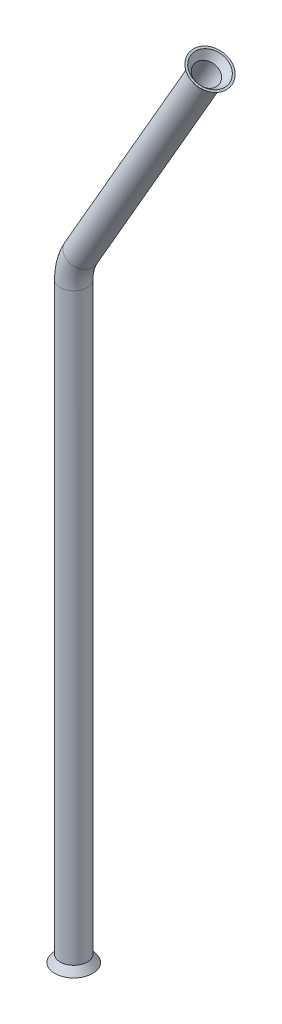
SolidWorks part; units mm, degrees
material "6061-T6 (SS)"
ref_plane "Front Plane" through (0, 0, 0) normal (0, 0, 1) x (1, 0, 0)
ref_plane "Top Plane" through (0, 0, 0) normal (0, 1, 0) x (1, 0, 0)
ref_plane "Right Plane" through (0, 0, 0) normal (1, 0, 0) x (0, 0, -1)
sketch "Sketch1" plane through (0, 0, 0) normal (0, 1, 0) x (1, 0, 0)
  circle A0 centre (0, 0) radius 4.826
  circle A1 centre (0, 0) radius 4.064
  dimension "D1" = 9.652
  dimension "D2" = 8.128
sketch "Sketch2" plane through (0, 0, 0) normal (0, 0, 1) x (1, 0, 0)
  line L0 (0, 0) -> (0, 206.9569)
  line L1 (2.5522, 216.4819) -> (47.0022, 293.4716)
  arc A0 (0, 206.9569) -> (2.5522, 216.4819) centre (19.05, 206.9569) cw
  point P5 (17.6445, 133.3712)
  point P7 (0, 91.9861)
  point P8 (10.8024, 130.8754)
  dimension "D1" = 44.45
  dimension "D2" = 150
  dimension "D4" = 293.4716
  dimension "D3" = 19.05
sweep "Sweep1" add profiles "Sketch1" path "Sketch2"
sketch "Sketch3" plane through (0, 0, 0) normal (0, -1, 0) x (1, 0, 0)
  circle A0 centre (0, 0) radius 4.826
  circle A1 centre (0, 0) radius 4.826 construction
extrude "Boss-Extrude1" add sketch "Sketch3" along normal blind 2.54 draft 37 draft outward yes
sketch "Sketch4" plane through (0, -2.54, 0) normal (0, -1, 0) x (1, 0, 0)
  line L0 (-4.826, 0) -> (-4.064, 0) construction
  line L1 (-5.978, 0) -> (-6.74, 0) construction
  circle A0 centre (0, 0) radius 5.978
  circle A1 centre (0, 0) radius 4.826 construction
  circle A2 centre (0, 0) radius 4.064 construction
  circle A3 centre (0, 0) radius 6.74 construction
extrude "Cut-Extrude1" cut sketch "Sketch4" against normal through all draft 37
sketch "Sketch5" plane through (138.8275, 240.4563, 0) normal (0.5, 0.866, 0) x (0, 0, -1)
  circle A1 centre (0, 106.0307) radius 4.826
  circle A2 centre (0, 106.0307) radius 4.826 construction
  circle A3 centre (0, 106.0307) radius 4.826 construction
extrude "Boss-Extrude2" add sketch "Sketch5" along normal blind 2.54 draft 37 draft outward yes
sketch "Sketch6" plane through (140.0975, 242.656, 0) normal (0.5, 0.866, 0) x (0, 0, -1)
  line L0 (-5.978, 106.0307) -> (-6.74, 106.0307) construction
  circle A0 centre (0, 106.0307) radius 5.978
  circle A1 centre (0, 106.0307) radius 6.74 construction
  dimension "D1" = 0.762
extrude "Cut-Extrude2" cut sketch "Sketch6" against normal through all draft 37
